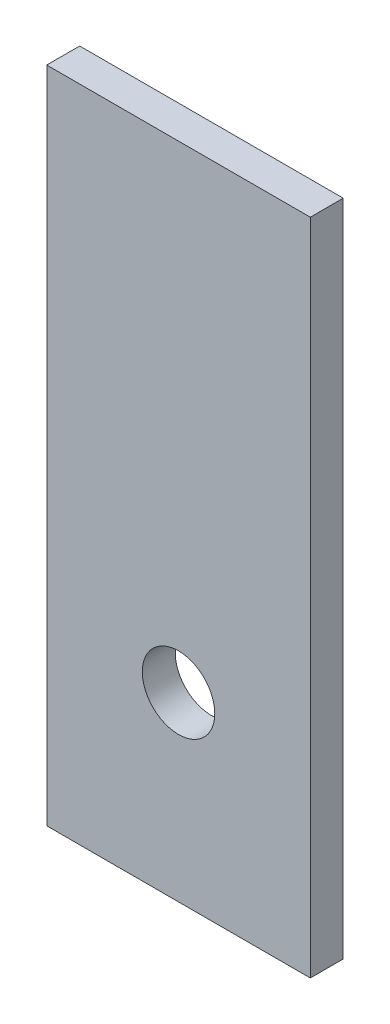
SolidWorks part; units mm, degrees
material "PLA"
ref_plane "Alzado" through (0, 0, 0) normal (0, 0, 1) x (1, 0, 0)
ref_plane "Planta" through (0, 0, 0) normal (0, 1, 0) x (1, 0, 0)
ref_plane "Vista lateral" through (0, 0, 0) normal (1, 0, 0) x (0, 0, -1)
sketch "Croquis1" plane through (0, 0, 0) normal (0, 0, 1) x (1, 0, 0)
  line L1 (0, 0) -> (80, 0)
  line L2 (0, 0) -> (0, 200)
  line L3 (0, 200) -> (80, 200)
  line L4 (80, 0) -> (80, 200)
  circle A0 centre (40, 55) radius 11
  dimension "D4" = 22
  dimension "D5" = 40
  dimension "D1" = 200
  dimension "D2" = 80
  dimension "D3" = 55
extrude "Saliente-Extruir1" add sketch "Croquis1" along normal blind 10
